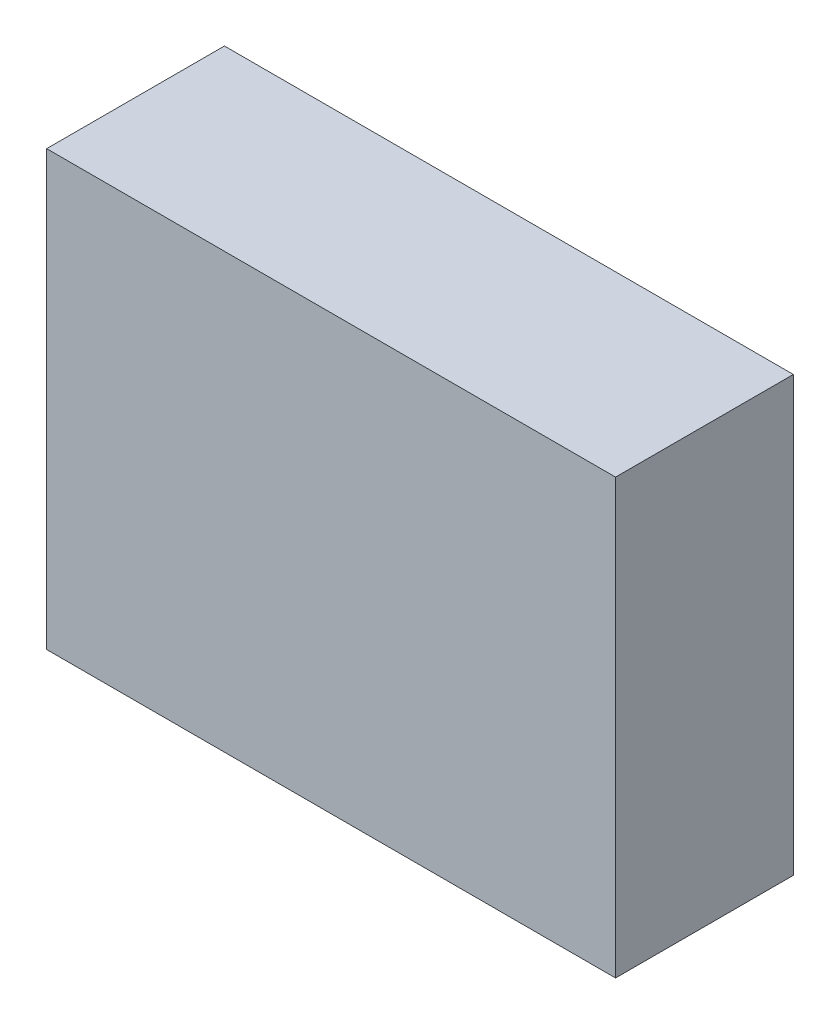
SolidWorks part; units mm, degrees
ref_plane "Plano frontal" through (0, 0, 0) normal (0, 0, 1) x (1, 0, 0)
ref_plane "Plano superior" through (0, 0, 0) normal (0, 1, 0) x (1, 0, 0)
ref_plane "Plano direito" through (0, 0, 0) normal (1, 0, 0) x (0, 0, -1)
sketch "Esboço1" plane through (0, 0, 0) normal (0, 0, 1) x (1, 0, 0)
  line L1 (8, -6.1) -> (-8, -6.1)
  line L2 (8, -6.1) -> (8, 6.1)
  line L3 (8, 6.1) -> (-8, 6.1)
  line L4 (-8, -6.1) -> (-8, 6.1)
  line L5 (8, -6.1) -> (-8, 6.1) construction
  line L6 (8, 6.1) -> (-8, -6.1) construction
  point P0 (0, 0)
  dimension "D1" = 16
  dimension "D2" = 12.2
extrude "Ressalto-extrusão1" add sketch "Esboço1" along normal blind 5
sketch "Esboço2" plane through (0, 0, 5) normal (0, 0, 1) x (1, 0, 0)
  line L0 (0, 0) -> (8, 0)
  line L1 (8, -6.1) -> (8, 6.1) construction
  line L2 (0, -6.1) -> (8, -6.1)
  line L3 (-8, -6.1) -> (8, -6.1) construction
